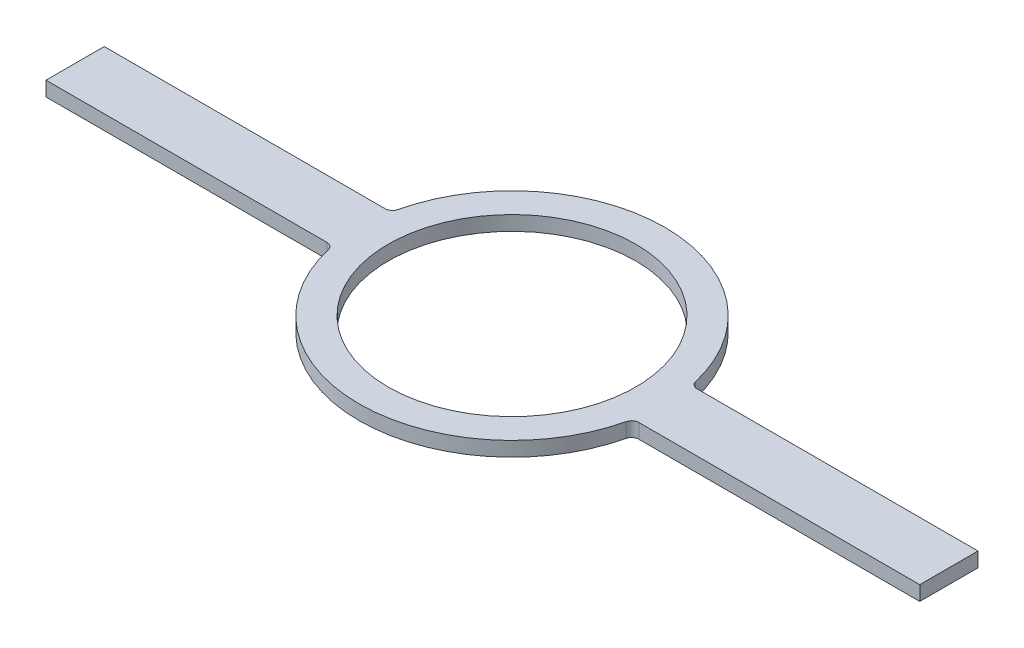
SolidWorks part; units mm, degrees
material "6061-T6 (SS)"
ref_plane "Front Plane" through (0, 0, 0) normal (0, 0, 1) x (1, 0, 0)
ref_plane "Top Plane" through (0, 0, 0) normal (0, 1, 0) x (1, 0, 0)
ref_plane "Right Plane" through (0, 0, 0) normal (1, 0, 0) x (0, 0, -1)
sketch "Sketch1" plane through (0, 0, 0) normal (0, 1, 0) x (1, 0, 0)
  line L0 (65.4543, 12.7) -> (190.5, 12.7)
  line L1 (-190.5, 12.7) -> (-65.4543, 12.7)
  line L2 (-190.5, 12.7) -> (-190.5, -12.7)
  line L3 (-190.5, -12.7) -> (-65.4543, -12.7)
  line L4 (190.5, 12.7) -> (190.5, -12.7)
  line L5 (-190.5, 12.7) -> (190.5, -12.7) construction
  line L6 (-190.5, -12.7) -> (190.5, 12.7) construction
  line L7 (65.4543, -12.7) -> (190.5, -12.7)
  circle A0 centre (0, 0) radius 53.975
  arc A1 (-65.4543, -12.7) -> (65.4543, -12.7) centre (0, 0) ccw
  arc A2 (65.4543, 12.7) -> (-65.4543, 12.7) centre (0, 0) ccw
  point P0 (0, 0)
  dimension "D3" = 107.95
  dimension "D4" = 12.7
  dimension "D1" = 381
  dimension "D2" = 25.4
extrude "Boss-Extrude1" add sketch "Sketch1" along normal blind 6.35
fillet "Fillet1" radius 3.175 4 edges at (-65.4543, 3.175, -12.7) (65.4543, 3.175, -12.7) (65.4543, 3.175, 12.7) (-65.4543, 3.175, 12.7)
